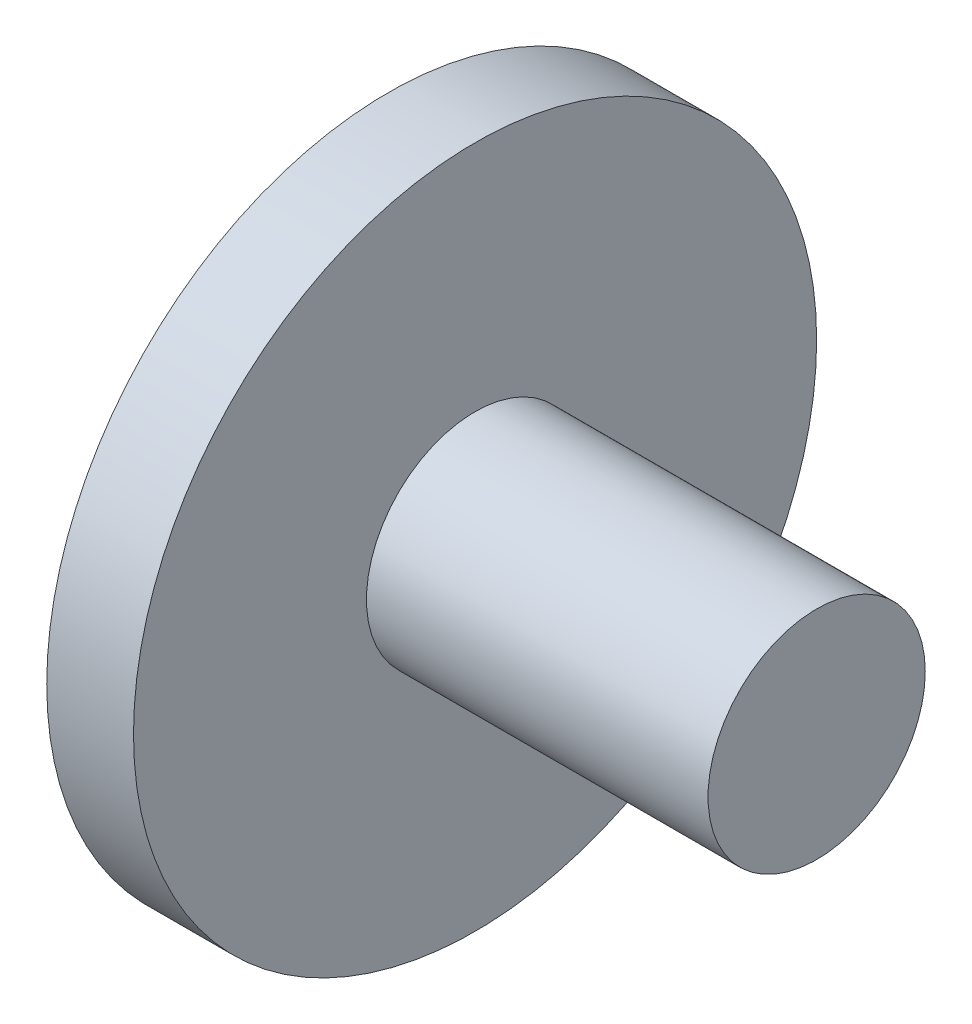
SolidWorks part; units mm, degrees
ref_plane "Front Plane" through (0, 0, 0) normal (1, 0, 0) x (0, 1, 0)
ref_plane "Top Plane" through (0, 0, 0) normal (0, 0, 1) x (0, 1, 0)
ref_plane "Right Plane" through (0, 0, 0) normal (0, 1, 0) x (-1, 0, 0)
sketch "Sketch1" plane through (0, 0, 0) normal (1, 0, 0) x (0, 1, 0)
  circle A0 centre (0, 0) radius 15
  circle A1 centre (0, 0) radius 50
  dimension "D1" = 30
  dimension "D2" = 100
extrude "Boss-Extrude1" add sketch "Sketch1" against normal blind 12.7 contours A1
sketch "Sketch3" plane through (0, 0, 0) normal (1, 0, 0) x (0, 0, -1)
  circle A0 centre (0, 0) radius 15.8989
  dimension "D1" = 31.7977
extrude "Boss-Extrude2" add sketch "Sketch3" along normal blind 50
